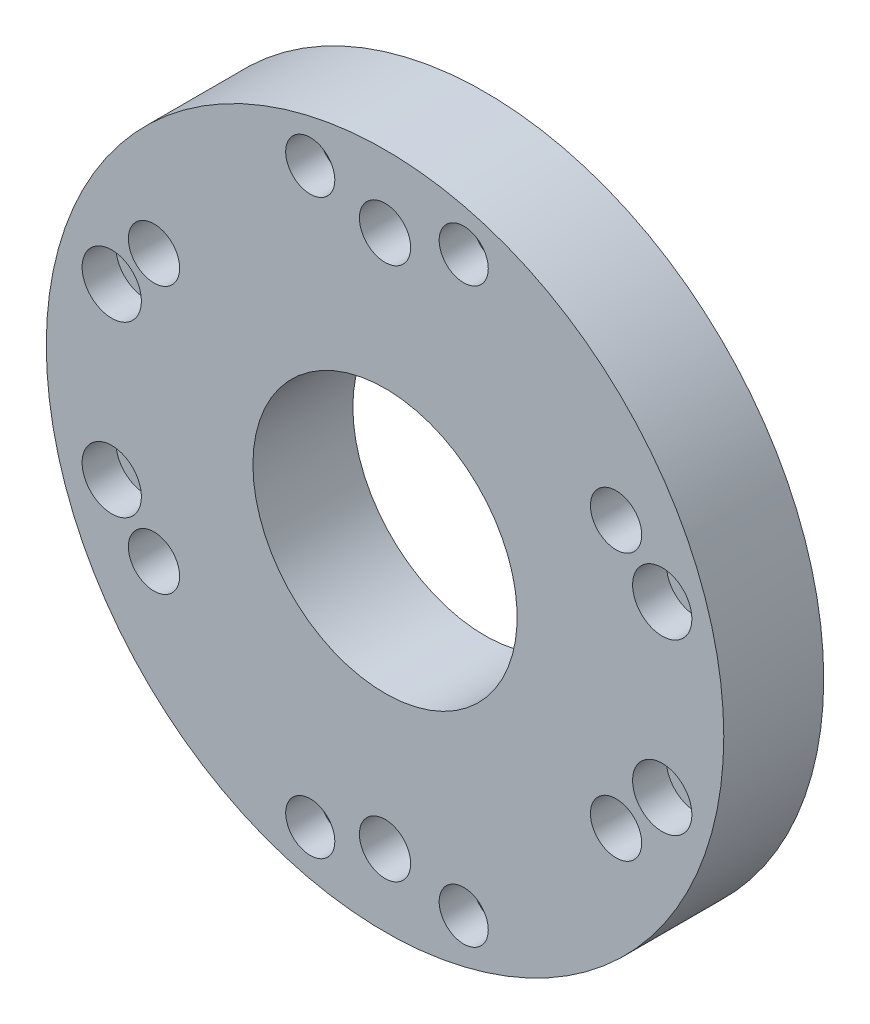
SolidWorks part; units mm, degrees
ref_plane "前视基准面" through (0, 0, 0) normal (0, 0, 1) x (1, 0, 0)
ref_plane "上视基准面" through (0, 0, 0) normal (0, 1, 0) x (1, 0, 0)
ref_plane "右视基准面" through (0, 0, 0) normal (1, 0, 0) x (0, 0, -1)
sketch "草图1" plane through (0, 0, 0) normal (0, 0, 1) x (1, 0, 0)
  circle A0 centre (0, 0) radius 40
  dimension "D1" = 80
extrude "凸台-拉伸1" add sketch "草图1" along normal blind 11.8
sketch "草图2" plane through (0, 0, 0) normal (0, 0, -1) x (-1, 0, 0)
  circle A0 centre (-32.7306, 10.1246) radius 2.15
  circle A1 centre (-32.7306, -9.8754) radius 2.15
  circle A2 centre (32.2694, -9.8754) radius 2.15
  circle A3 centre (32.2694, 10.1246) radius 2.15
  circle A4 centre (-9.2906, 33.9346) radius 1.75
  circle A5 centre (8.8294, 33.9346) radius 1.75
  circle A6 centre (8.8294, -33.6854) radius 1.75
  circle A7 centre (-9.2906, -33.6854) radius 1.75
  dimension "D1" = 4.3
  dimension "D2" = 3.5
  dimension "D3" = 3.5
  dimension "D4" = 3.5
  dimension "D5" = 3.5
  dimension "D6" = 4.3
  dimension "D7" = 4.3
  dimension "D8" = 4.3
extrude "切除-拉伸1" cut sketch "草图2" against normal through all
sketch "草图3" plane through (0, 0, 0) normal (0, 0, -1) x (-1, 0, 0)
  line L0 (0, 0) -> (0, 41.6751) construction
  circle A0 centre (0, 0) radius 31.5 construction
  circle A1 centre (0, 31.5) radius 3.025
  circle A2 centre (27.2798, 15.75) radius 3.025
  circle A3 centre (27.2798, -15.75) radius 3.025
  circle A4 centre (0, -31.5) radius 3.025
  circle A5 centre (-27.2798, -15.75) radius 3.025
  circle A6 centre (-27.2798, 15.75) radius 3.025
  circle A7 centre (0, 0) radius 15.6
  point P20 (0, 0)
  dimension "D1" = 63
  dimension "D2" = 6.05
  dimension "D4" = 31.2
  dimension "D3" = 6
extrude "切除-拉伸2" cut sketch "草图3" against normal through all
sketch "草图5" plane through (0, 0, 11.8) normal (0, 0, 1) x (1, 0, 0)
  circle A0 centre (-8.8294, -33.6854) radius 2.9
  circle A1 centre (-8.8294, 33.9346) radius 2.9
  circle A2 centre (-32.2694, 10.1246) radius 3.5
  circle A3 centre (-32.2694, -9.8754) radius 3.5
  circle A4 centre (9.2906, 33.9346) radius 2.9
  circle A5 centre (32.7306, 10.1246) radius 3.5
  circle A6 centre (32.7306, -9.8754) radius 3.5
  circle A7 centre (9.2906, -33.6854) radius 2.9
  dimension "D1" = 5.8
  dimension "D2" = 7
  dimension "D3" = 7
  dimension "D4" = 5.8
  dimension "D5" = 5.8
  dimension "D6" = 7
  dimension "D7" = 7
  dimension "D8" = 5.8
extrude "切除-拉伸4" cut sketch "草图5" against normal blind 4
